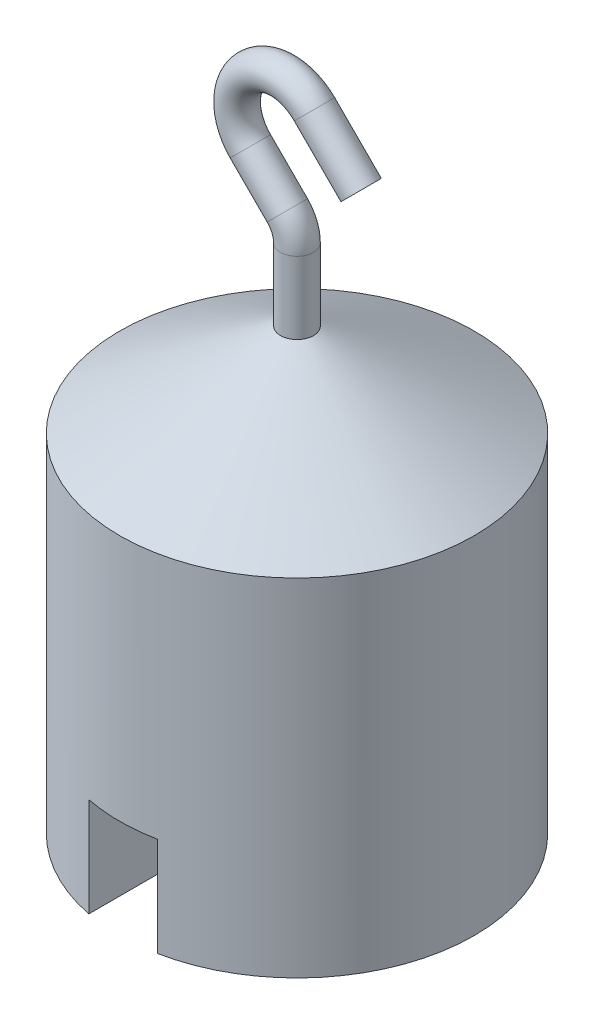
SolidWorks part; units mm, degrees
ref_plane "Front Plane" through (0, 0, 0) normal (0, 0, 1) x (1, 0, 0)
ref_plane "Top Plane" through (0, 0, 0) normal (0, 1, 0) x (1, 0, 0)
ref_plane "Right Plane" through (0, 0, 0) normal (1, 0, 0) x (0, 0, -1)
sketch "Sketch1" plane through (0, 0, 0) normal (0, 0, 1) x (1, 0, 0)
  line L0 (0, 0) -> (0, 42)
  line L1 (0, 42) -> (19.5, 53.2583)
  line L2 (19.5, 53.2583) -> (21.5, 53.2583)
  line L3 (21.5, 53.2583) -> (21.5, 0)
  line L4 (21.5, 0) -> (0, 0)
  dimension "D1" = 42
  dimension "D2" = 2
  dimension "D3" = 120
  dimension "D4" = 21.5
revolve "Revolve1" add sketch "Sketch1" angle 360 about L3
sketch "Sketch2" plane through (0, 53.2583, 0) normal (0, 1, 0) x (1, 0, 0)
  circle A0 centre (21.5, 0) radius 2
  dimension "D1" = 4
sketch "Sketch3" plane through (0, 0, 0) normal (0, 0, 1) x (1, 0, 0)
  line L0 (20.3284, 64.8299) -> (15.8431, 69.3152)
  line L1 (23.5, 53.2583) -> (19.5, 53.2583) construction
  line L2 (23.6213, 77.0934) -> (29.2782, 71.4365)
  line L3 (21.5, 53.2583) -> (21.5, 62.0015)
  arc A0 (15.8431, 69.3152) -> (23.6213, 77.0934) centre (19.7322, 73.2043) cw
  arc A1 (20.3284, 64.8299) -> (21.5, 62.0015) centre (17.5, 62.0015) cw
  point P12 (21.5, 63.6583)
  dimension "D3" = 5.5
  dimension "D6" = 4
  dimension "D1" = 45
  dimension "D2" = 8
  dimension "D4" = 8
  dimension "D5" = 10.4
sweep "Sweep6" add profiles "Sketch2" path "Sketch3"
sketch "Sketch10" plane through (0, 0, 0) normal (0, 0, 1) x (1, 0, 0)
  line L0 (0, 0) -> (43, 0) construction
  line L1 (17.35, 0) -> (25.65, 0)
  line L2 (17.35, 0) -> (17.35, 12)
  line L3 (17.35, 12) -> (25.65, 12)
  line L4 (25.65, 0) -> (25.65, 12)
  line L5 (21.5, 12) -> (21.5, 0) construction
  line L6 (0, 0) -> (43, 0) construction
  point P12 (21.5, 0)
  dimension "D1" = 12
  dimension "D2" = 8.3
extrude "Cut-Extrude1" cut sketch "Sketch10" against normal through all both and the other way through all
sketch "Sketch11" plane through (25.65, 0, 0) normal (-1, 0, 0) x (0, 0, 1)
  line L0 (0, -23.65) -> (0, 23.65) construction
  line L1 (-21.0957, 0) -> (21.0957, 0) construction
  circle A0 centre (0, 4.5) radius 1.5
  dimension "D1" = 3
  dimension "D2" = 4.5
extrude "Boss-Extrude1" add sketch "Sketch11" along normal up to next
sketch "Sketch12" plane through (0, 0, 0) normal (0, 0, 1) x (1, 0, 0)
  line L0 (23.5, 53.2583) -> (44.511, 74.2693) construction
  line L1 (23.5, 53.2583) -> (46.6392, 53.2583) construction
  dimension "D1" = 45
ref_plane "Plane1" through (0, 0, 0) normal (-1, 0, 0) x (0, 0, 1)
sketch "Sketch13" plane through (0, 0, 0) normal (-1, 0, 0) x (0, 0, 1)
  line L0 (0, 27) -> (0, 0) construction
  line L1 (-7.5, 33) -> (7.5, 33)
  line L2 (-7.5, 33) -> (-7.5, 27)
  line L3 (-7.5, 27) -> (7.5, 27)
  line L4 (7.5, 33) -> (7.5, 27)
  line L5 (21.5, 42) -> (-21.5, 42) construction
  dimension "D1" = 15
  dimension "D2" = 6
  dimension "D3" = 9
extrude "Cut-Extrude2" cut sketch "Sketch13" against normal blind 1.25
sketch "Sketch14" plane through (1.25, 0, 0) normal (-1, 0, 0) x (0, 0, 1)
  line L0 (-7.2241, 28) -> (7.2241, 28) construction
  line L1 (-7.2241, 28) -> (-7.2241, 27) construction
  line L2 (7.2241, 28) -> (7.2241, 27) construction
  line L3 (7.2241, 27) -> (-7.2241, 27) construction
  line L4 (4.3978, 29.2) -> (6.4889, 29.2) construction
  text T0 "500"
  text T1 "0" font "Century Gothic" height in points 8
  point P11 (4.3978, 29)
  point P12 (0, 0)
  point P13 (6.8458, 29.2)
  point P14 (0, 0)
  point P15 (6.4889, 29.2)
  dimension "D1" = 1
  dimension "D2" = 1.2
extrude "Cut-Extrude3" cut sketch "Sketch14" against normal blind 0.5
